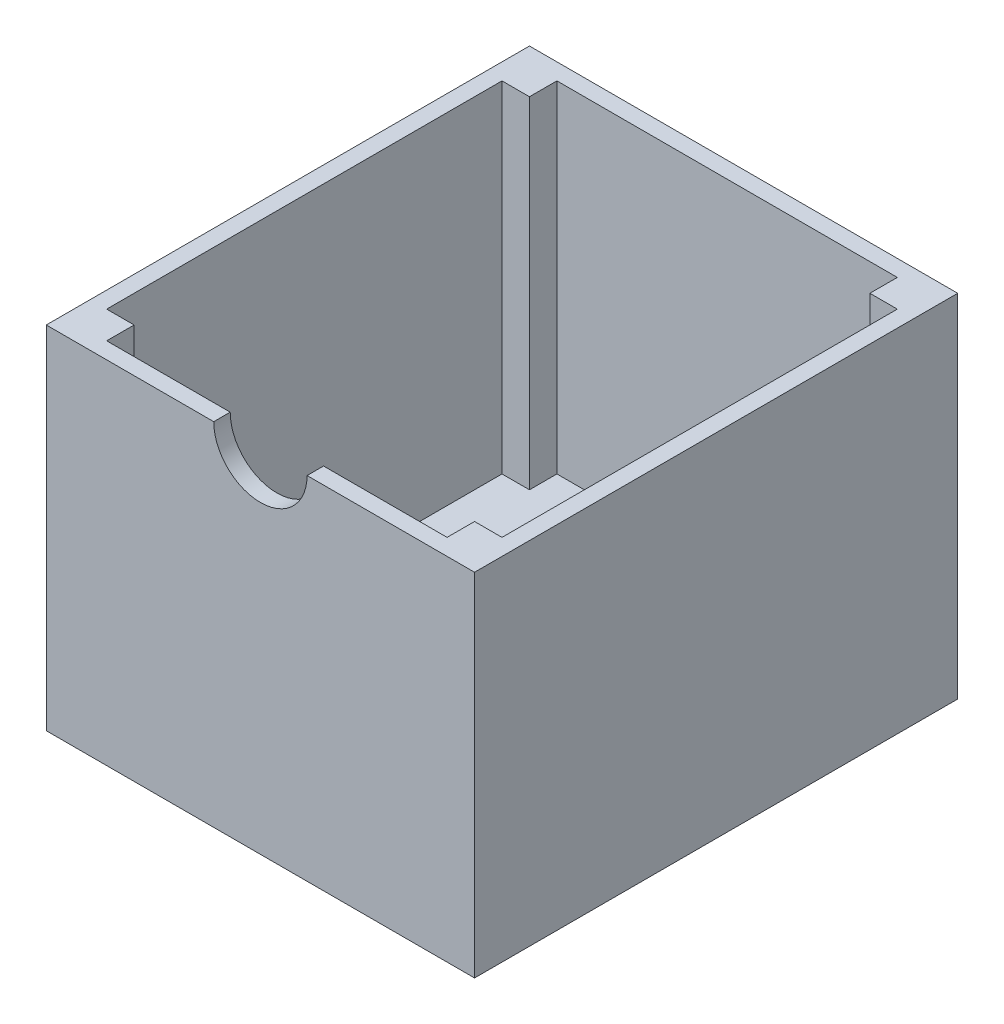
SolidWorks part; units mm, degrees
ref_plane "Front Plane" through (0, 0, 0) normal (0, 0, 1) x (1, 0, 0)
ref_plane "Top Plane" through (0, 0, 0) normal (0, 1, 0) x (1, 0, 0)
ref_plane "Right Plane" through (0, 0, 0) normal (1, 0, 0) x (0, 0, -1)
sketch "Sketch1" plane through (0, 0, 0) normal (0, 1, 0) x (1, 0, 0)
  line L0 (0, 0) -> (0, 82)
  line L1 (0, 82) -> (72, 82)
  line L2 (72, 82) -> (72, 0)
  line L3 (72, 0) -> (0, 0)
  dimension "D1" = 82
  dimension "D2" = 72
extrude "Boss-Extrude1" add sketch "Sketch1" along normal blind 2
sketch "Sketch2" plane through (0, 2, 0) normal (0, 1, 0) x (1, 0, 0)
  line L0 (5, 82) -> (67, 82)
  line L1 (72, 77) -> (72, 5)
  line L4 (67, 0) -> (5, 0)
  line L5 (0, 5) -> (0, 77)
  line L6 (-3, 85) -> (75, 85)
  line L7 (75, 85) -> (75, -3)
  line L8 (75, -3) -> (-3, -3)
  line L9 (-3, -3) -> (-3, 85)
  line L10 (5, 82) -> (5, 77)
  line L11 (5, 77) -> (0, 77)
  line L12 (67, 82) -> (67, 77)
  line L13 (67, 77) -> (72, 77)
  line L14 (5, 0) -> (5, 5)
  line L15 (5, 5) -> (0, 5)
  line L16 (67, 0) -> (67, 5)
  line L17 (67, 5) -> (72, 5)
  line L18 (0, 0) -> (0, 82) construction
  line L19 (0, 82) -> (72, 82) construction
  line L20 (72, 82) -> (72, 0) construction
  line L21 (72, 0) -> (0, 0) construction
  dimension "D1" = 3
  dimension "D2" = 5
  dimension "D3" = 5
  dimension "D4" = 5
  dimension "D5" = 5
  dimension "D6" = 5
  dimension "D7" = 5
  dimension "D8" = 5
  dimension "D9" = 5
extrude "Boss-Extrude2" add sketch "Sketch2" along normal blind 64 from surface at -2 starting at face at (36, 0, -41)
sketch "Sketch4" plane through (0, 0, 3) normal (0, 0, 1) x (1, 0, 0)
  line L0 (75, 64) -> (-3, 64) construction
  circle A0 centre (36, 64) radius 8.5
  dimension "D1" = 17
extrude "Cut-Extrude1" cut sketch "Sketch4" against normal up to surface (3 mm away) up to face at (36, 33, 0)
